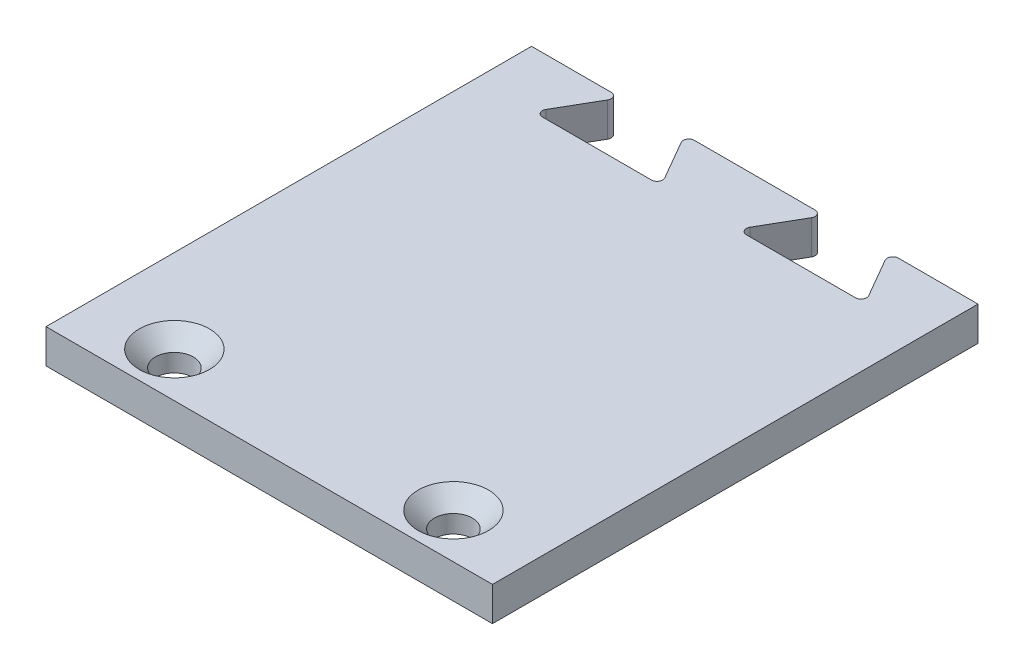
SolidWorks part; units mm, degrees
ref_plane "Front Plane" through (0, 0, 0) normal (0, 0, 1) x (1, 0, 0)
ref_plane "Top Plane" through (0, 0, 0) normal (0, 1, 0) x (1, 0, 0)
ref_plane "Right Plane" through (0, 0, 0) normal (1, 0, 0) x (0, 0, -1)
sketch "Sketch1" plane through (0, 0, 0) normal (0, 1, 0) x (1, 0, 0)
  line L0 (0, 0) -> (0, 43.5)
  line L1 (0, 43.5) -> (8, 43.5)
  line L2 (8, 43.5) -> (5.1132, 38.5)
  line L3 (5.1132, 38.5) -> (16.6132, 38.5)
  line L4 (16.6132, 38.5) -> (13.7265, 43.5)
  line L5 (13.7265, 43.5) -> (26.2735, 43.5)
  line L6 (26.2735, 43.5) -> (23.3868, 38.5)
  line L7 (23.3868, 38.5) -> (34.8868, 38.5)
  line L8 (34.8868, 38.5) -> (32, 43.5)
  line L9 (32, 43.5) -> (40, 43.5)
  line L10 (40, 43.5) -> (40, 0)
  line L11 (40, 0) -> (0, 0)
  dimension "D1" = 43.5
  dimension "D2" = 40
  dimension "D3" = 8
  dimension "D4" = 11.5
  dimension "D5" = 11.5
  dimension "D6" = 8
  dimension "D7" = 5
  dimension "D8" = 5
  dimension "D9" = 5
  dimension "D10" = 5
  dimension "D11" = 60
  dimension "D12" = 60
  dimension "D13" = 60
extrude "Boss-Extrude1" add sketch "Sketch1" along normal blind 3.05
fillet "Fillet3" radius 0.5 8 edges at (34.8868, 1.525, -38.5) (32, 1.525, -43.5) (23.3868, 1.525, -38.5) (26.2735, 1.525, -43.5) (13.7265, 1.525, -43.5) (16.6132, 1.525, -38.5) (5.1132, 1.525, -38.5) (8, 1.525, -43.5)
hole_wizard "CSK for M3 Flat Head Machine Screw1" positions "Sketch6" profile "Sketch7" countersink size "M3" standard "ANSI Metric" end condition through all
sketch "Sketch6" plane through (0, 3.05, 0) normal (0, 1, 0) x (1, 0, 0)
  line L0 (0, 43.5) -> (0, 0) construction
  line L1 (40, 0) -> (40, 43.5) construction
  line L2 (0, 4) -> (40, 4) construction
  line L4 (0, 0) -> (40, 0) construction
  point P0 (7.5, 4)
  point P2 (32.5, 4)
  dimension "D1" = 7.5
  dimension "D2" = 7.5
  dimension "D3" = 4
sketch "Sketch7" plane through (7.5, 3.05, -4) normal (1, 0, 0) x (0, 0, 1)
  line L0 (0, 0) -> (0, 3.05)
  line L1 (0, 3.05) -> (1.7, 3.05)
  line L2 (1.7, 3.05) -> (1.7, 1.45)
  line L3 (1.7, 1.45) -> (3.15, 0)
  line L5 (3.15, 0) -> (0, 0)
  line L6 (-1.7, 1.45) -> (-3.15, 0) construction
  line L11 (0, -6.35) -> (0, 107.95) construction
  dimension "Thru Hole Dia." = 3.4
  dimension "Thru Hole Depth" = 3.05
  dimension "Near C'Sink Dia." = 6.3
  dimension "Near C'Sink Angle" = 90
